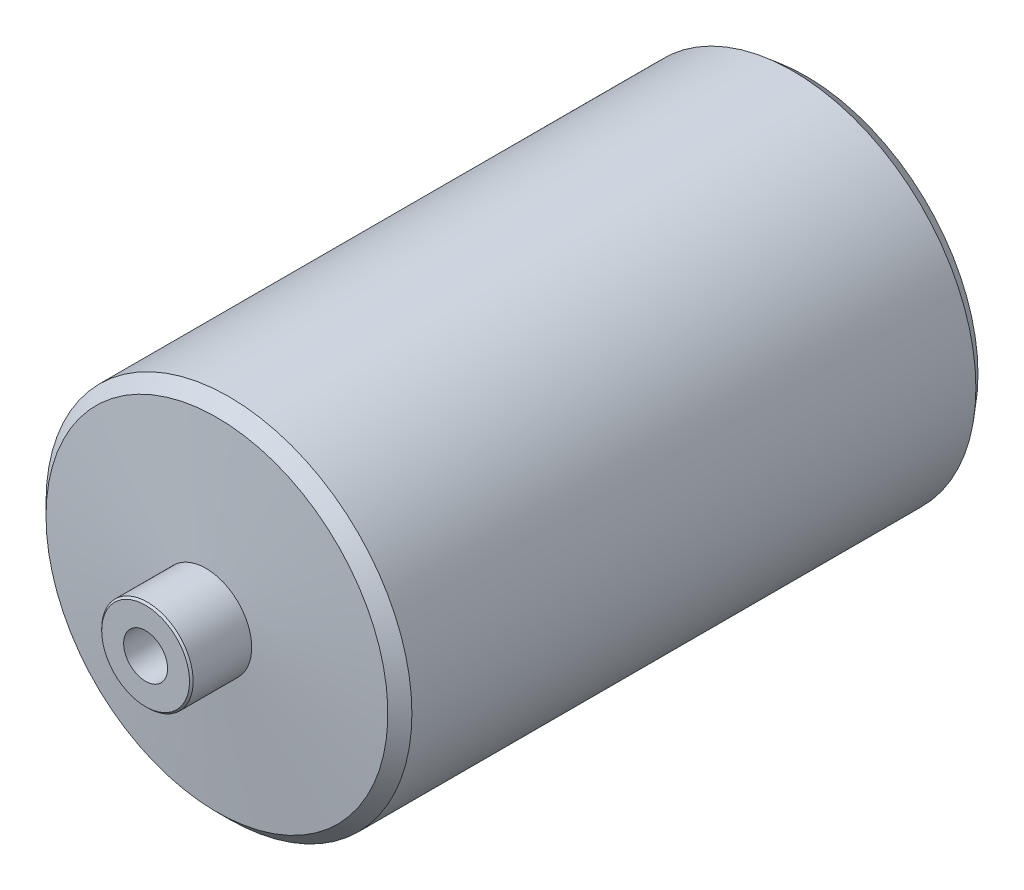
SolidWorks part; units mm, degrees
ref_plane "Alzado" through (0, 0, 0) normal (0, 0, 1) x (1, 0, 0)
ref_plane "Planta" through (0, 0, 0) normal (0, 1, 0) x (1, 0, 0)
ref_plane "Vista lateral" through (0, 0, 0) normal (1, 0, 0) x (0, 0, -1)
sketch "Croquis1" plane through (0, 0, 0) normal (1, 0, 0) x (0, 0, -1)
  line L0 (0, 0) -> (0, 12.5)
  line L1 (0, 12.5) -> (-16.5, 12.5)
  line L3 (-19.7808, 50) -> (-180.2192, 50)
  line L5 (-183.5, 12.5) -> (-200, 12.5)
  line L6 (-200, 12.5) -> (-200, 0)
  line L7 (-200, 0) -> (0, 0)
  line L8 (-19.7808, 50) -> (-16.5, 12.5)
  line L9 (-183.5, 12.5) -> (-180.2192, 50)
  dimension "D1" = 12.5
  dimension "D2" = 16.5
  dimension "D3" = 50
  dimension "D4" = 85
  dimension "D5" = 200
  dimension "D6" = 16.5
  dimension "D7" = 85
  dimension "D8" = 12.5
revolve "Revolución2" add sketch "Croquis1" angle 360 about L7
chamfer "Chaflán1" distance 3 angle 45 2 edges at (50, 0, 180.2192) (50, 0, 19.7808)
hole_wizard "Taladro de margen para M101" positions "Croquis4" profile "Croquis5" hole size "M10" standard "DIN"
sketch "Croquis4" plane through (0, 0, 0) normal (0, 0, -1) x (-1, 0, 0)
  point P0 (0, 0)
sketch "Croquis5" plane through (0, 0, 0) normal (1, 0, 0) x (0, 1, 0)
  line L0 (0, 0) -> (0, 59)
  line L1 (0, 59) -> (6, 55.3948)
  line L2 (6, 55.3948) -> (6, 0)
  line L5 (6, 0) -> (0, 0)
  line L10 (0, 59) -> (-6, 55.3948) construction
  line L11 (0, -6.35) -> (0, 107.95) construction
  dimension "Diámetro de taladro" = 12
  dimension "Profundidad de taladro" = 59
  dimension "Ángulo de perforador" = 118
hole_wizard "Taladro de margen para M102" positions "Croquis6" profile "Croquis7" hole size "M10" standard "DIN"
sketch "Croquis6" plane through (0, 0, 200) normal (0, 0, 1) x (1, 0, 0)
  point P0 (0, 0)
sketch "Croquis7" plane through (0, 0, 200) normal (1, 0, 0) x (0, -1, 0)
  line L0 (0, 0) -> (0, 59)
  line L1 (0, 59) -> (6, 55.3948)
  line L2 (6, 55.3948) -> (6, 0)
  line L5 (6, 0) -> (0, 0)
  line L10 (0, 59) -> (-6, 55.3948) construction
  line L11 (0, -6.35) -> (0, 107.95) construction
  dimension "Diámetro de taladro" = 12
  dimension "Profundidad de taladro" = 59
  dimension "Ángulo de perforador" = 118
chamfer "Chaflán2" distance 0.5 angle 45 2 edges at (12.5, 0, 0) (12.5, 0, 200)
